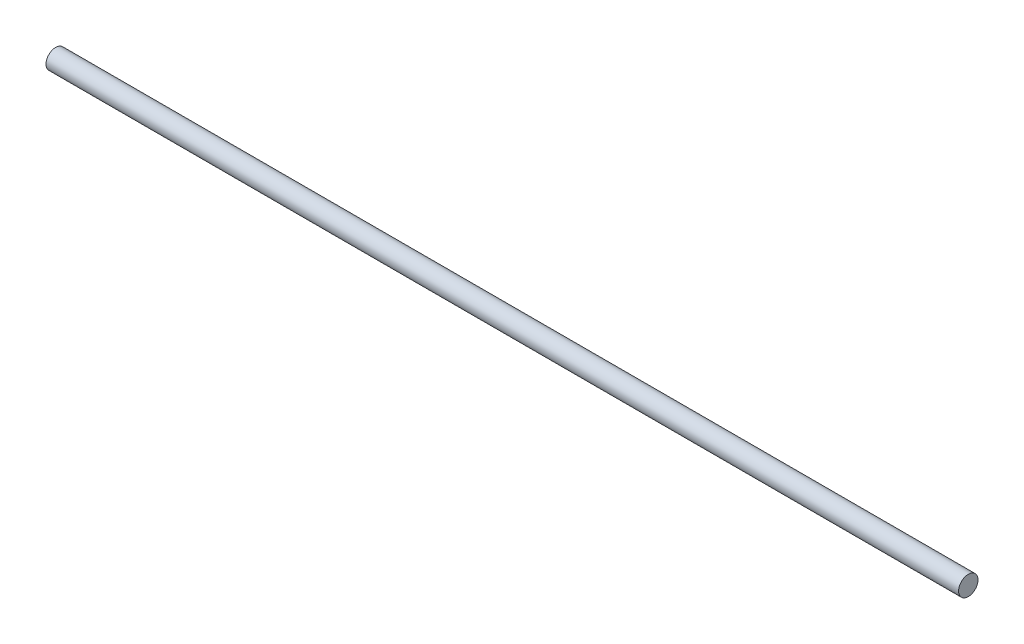
SolidWorks part; units mm, degrees
ref_plane "Ön Düzlem" through (0, 0, 0) normal (0, 0, 1) x (1, 0, 0)
ref_plane "Üst Düzlem" through (0, 0, 0) normal (0, 1, 0) x (1, 0, 0)
ref_plane "Sağ Düzlem" through (0, 0, 0) normal (1, 0, 0) x (0, 0, -1)
sketch "Sketch4" plane through (0, 0, 0) normal (1, 0, 0) x (0, 0, -1)
  circle A0 centre (-1405.7929, -82.4347) radius 20
  point P2 (0, 0)
  dimension "D1" = 40
extrude "Boss-Extrude2" add sketch "Sketch4" along normal blind 1880
